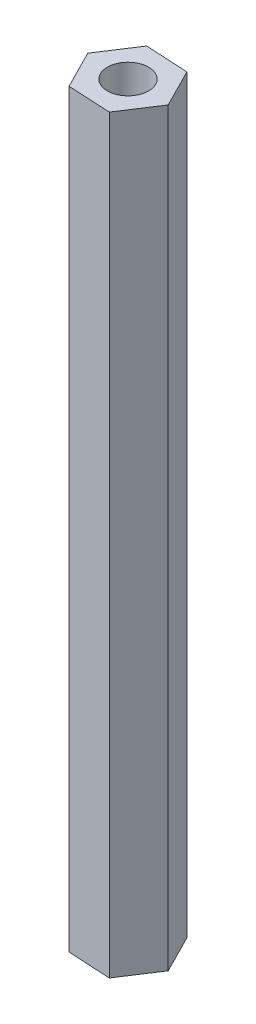
SolidWorks part; units mm, degrees
ref_plane "前视基准面" through (0, 0, 0) normal (0, 0, 1) x (1, 0, 0)
ref_plane "上视基准面" through (0, 0, 0) normal (0, 1, 0) x (1, 0, 0)
ref_plane "右视基准面" through (0, 0, 0) normal (1, 0, 0) x (0, 0, -1)
other "Configuration Table"
sketch "草图1" plane through (0, 0, 0) normal (0, 1, 0) x (1, 0, 0)
  line L1 (3.4015, -0.1819) -> (1.8583, 2.8548)
  line L2 (1.8583, 2.8548) -> (-1.5432, 3.0368)
  line L3 (-1.5432, 3.0368) -> (-3.4015, 0.1819)
  line L4 (-3.4015, 0.1819) -> (-1.8583, -2.8548)
  line L5 (-1.8583, -2.8548) -> (1.5432, -3.0368)
  line L6 (1.5432, -3.0368) -> (3.4015, -0.1819)
  circle A0 centre (0, 0) radius 2.95 construction
  dimension "D1" = 5.9
extrude "凸台-拉伸1" add sketch "草图1" along normal blind 60
hole_wizard "M4 螺纹孔1" positions "草图2" profile "草图3" tap size "M4" standard "GB" end condition through all
sketch "草图2" plane through (0, 60, 0) normal (0, 1, 0) x (1, 0, 0)
  point P0 (0, 0)
sketch "草图3" plane through (0, 60, 0) normal (1, 0, 0) x (0, 0, 1)
  line L0 (0, 0) -> (0, 60)
  line L1 (0, 60) -> (1.65, 60)
  line L2 (1.65, 60) -> (1.65, 0)
  line L5 (1.65, 0) -> (0, 0)
  line L11 (0, -6.35) -> (0, 107.95) construction
  dimension "通孔螺纹孔钻头直径" = 3.3
  dimension "通孔螺纹孔钻头深度" = 60
cosmetic thread "孔螺纹线1" parameters "D2"=4
